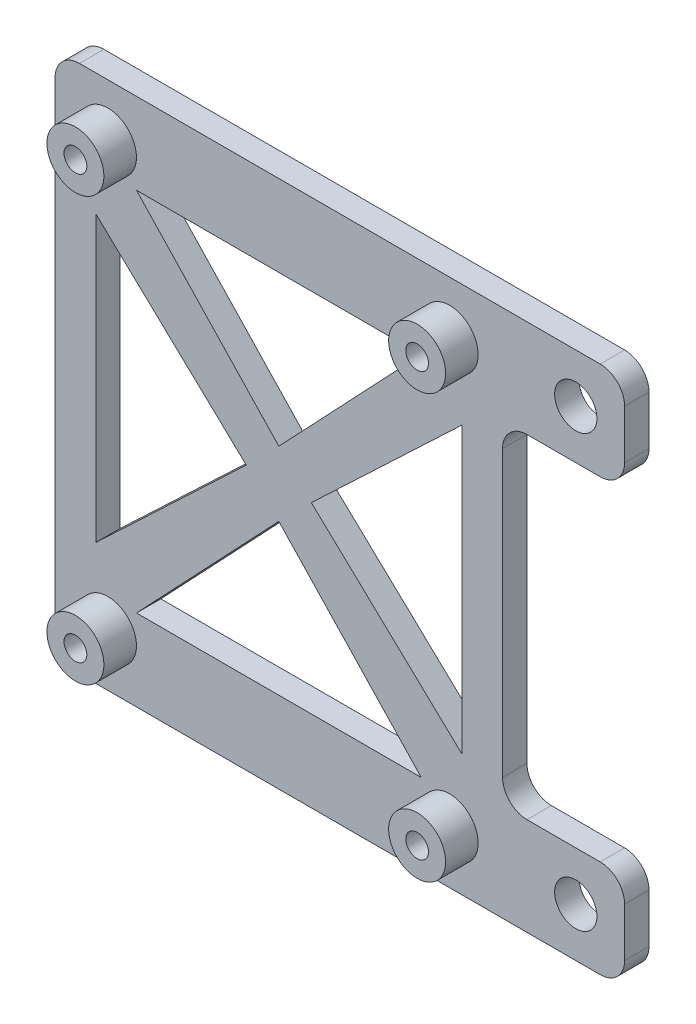
SolidWorks part; units mm, degrees
ref_plane "Front Plane" through (0, 0, 0) normal (0, 0, 1) x (1, 0, 0)
ref_plane "Top Plane" through (0, 0, 0) normal (0, 1, 0) x (1, 0, 0)
ref_plane "Right Plane" through (0, 0, 0) normal (1, 0, 0) x (0, 0, -1)
sketch "Sketch1" plane through (0, 0, 0) normal (0, 0, 1) x (1, 0, 0)
  line L1 (3, 0) -> (70, 0)
  line L2 (0, 3) -> (0, 62)
  line L3 (3, 65) -> (62, 65)
  line L4 (55, 15) -> (55, 50)
  line L5 (62, 65) -> (67, 65)
  line L7 (58, 53) -> (67, 53)
  line L8 (70, 62) -> (70, 56)
  line L9 (70, 0) -> (67, 0)
  line L11 (58, 12) -> (67, 12)
  line L12 (70, 3) -> (70, 9)
  arc A0 (3, 65) -> (0, 62) centre (3, 62) ccw
  arc A1 (0, 3) -> (3, 0) centre (3, 3) ccw
  arc A2 (70, 3) -> (67, 0) centre (67, 3) cw
  arc A3 (70, 9) -> (67, 12) centre (67, 9) ccw
  arc A4 (58, 12) -> (55, 15) centre (58, 15) cw
  arc A5 (67, 65) -> (70, 62) centre (67, 62) cw
  arc A6 (70, 56) -> (67, 53) centre (67, 56) cw
  arc A7 (58, 53) -> (55, 50) centre (58, 50) ccw
  circle A8 centre (64, 59) radius 2.6
  circle A9 centre (64, 6) radius 2.6
  point P13 (0, 65)
  point P16 (0, 0)
  point P25 (70, 65)
  point P28 (70, 53)
  point P31 (70, 59)
  point P38 (70, 6)
  dimension "D4" = 3
  dimension "D6" = 5.2
  dimension "D1" = 65
  dimension "D2" = 15
  dimension "D3" = 12
  dimension "D5" = 55
  dimension "D7" = 6
  dimension "D8" = 9
extrude "Boss-Extrude1" add sketch "Sketch1" along normal blind 3 contours A7 L7 A6 L8 A5 L5 L3 A0 L2 A1 L1 A2 L12 A3 L11 A4 L4 A9 A8
sketch "Sketch2" plane through (0, 0, 3) normal (0, 0, 1) x (1, 0, 0)
  line L7 (0, 3) -> (0, 62) construction
  line L8 (6.5, 58.5) -> (48.5, 58.5) construction
  line L9 (6.5, 58.5) -> (6.5, 6.5) construction
  line L10 (6.5, 6.5) -> (48.5, 6.5) construction
  line L11 (48.5, 58.5) -> (48.5, 6.5) construction
  circle A4 centre (6.5, 58.5) radius 3.5
  circle A5 centre (48.5, 58.5) radius 3.5
  circle A6 centre (6.5, 6.5) radius 3.5
  circle A7 centre (48.5, 6.5) radius 3.5
  point P7 (0, 32.5)
  point P10 (6.5, 32.5)
  dimension "D3" = 6.5
  dimension "D4" = 7
  dimension "D1" = 42
  dimension "D2" = 52
extrude "Boss-Extrude2" add sketch "Sketch2" along normal blind 4
sketch "Sketch3" plane through (0, 0, 3) normal (0, 0, 1) x (1, 0, 0)
  line L0 (10, 55) -> (45, 55)
  line L5 (27.5, 36.5) -> (27.5, 32.5) construction
  line L6 (45, 55) -> (27.5, 36.5)
  line L19 (27.5, 36.5) -> (10, 55)
  line L32 (0, 3) -> (0, 62) construction
  line L33 (55, 15) -> (55, 50) construction
  line L34 (3, 65) -> (67, 65) construction
  line L35 (50, 50) -> (50, 15)
  line L36 (50, 15) -> (31.5, 32.5)
  line L37 (31.5, 32.5) -> (50, 50)
  line L38 (31.5, 32.5) -> (27.5, 32.5) construction
  line L39 (45, 10) -> (10, 10)
  line L40 (10, 10) -> (27.5, 28.5)
  line L41 (27.5, 28.5) -> (45, 10)
  line L42 (27.5, 28.5) -> (27.5, 32.5) construction
  line L43 (5, 15) -> (5, 50)
  line L44 (5, 50) -> (23.5, 32.5)
  line L45 (23.5, 32.5) -> (5, 15)
  line L46 (23.5, 32.5) -> (27.5, 32.5) construction
  point P6 (27.5, 55)
  point P19 (0, 32.5)
  point P27 (27.5, 32.5)
  dimension "D1" = 10
  dimension "D2" = 10
  dimension "D3" = 10
  dimension "D4" = 4
  dimension "D5" = 4
extrude "Cut-Extrude1" cut sketch "Sketch3" against normal blind 3
sketch "Sketch4" plane through (0, 0, 7) normal (0, 0, 1) x (1, 0, 0)
  circle A4 centre (6.5, 58.5) radius 1.4
  circle A5 centre (48.5, 6.5) radius 1.4
  circle A6 centre (6.5, 6.5) radius 1.4
  circle A7 centre (48.5, 58.5) radius 1.4
  dimension "D1" = 2.8
extrude "Cut-Extrude2" cut sketch "Sketch4" against normal through all
